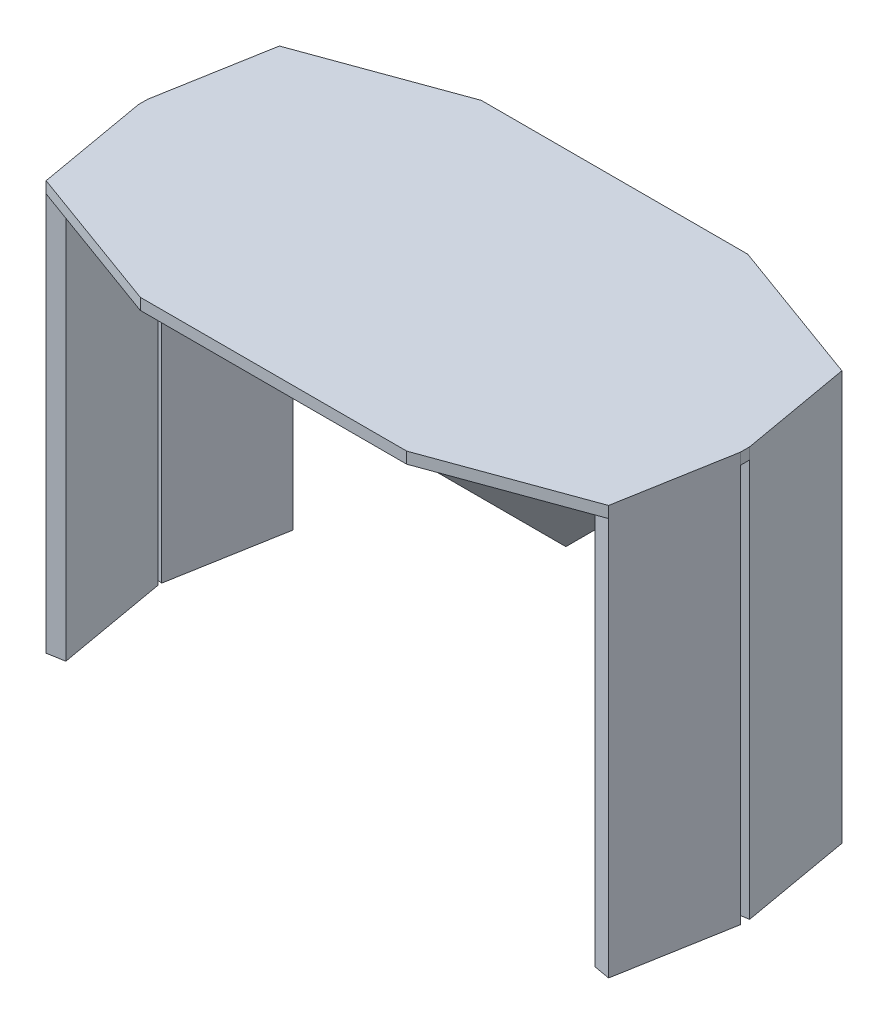
SolidWorks part; units mm, degrees
ref_plane "Front Plane" through (0, 0, 0) normal (0, 0, 1) x (1, 0, 0)
ref_plane "Top Plane" through (0, 0, 0) normal (0, 1, 0) x (1, 0, 0)
ref_plane "Right Plane" through (0, 0, 0) normal (1, 0, 0) x (0, 0, -1)
sketch "Sketch2" plane through (0, 0, 0) normal (1, 0, 0) x (0, 0, -1)
  line L0 (0, 0) -> (20, 28.563)
  line L1 (20, 28.563) -> (-20, 28.563)
  line L2 (-20, 28.563) -> (0, 0)
  dimension "D1" = 55
  dimension "D2" = 55
  dimension "D3" = 40
extrude "Boss-Extrude1" add sketch "Sketch2" along normal blind 100
sketch "Sketch3" plane through (0, 28.563, 0) normal (0, 1, 0) x (1, 0, 0)
  line L0 (96.527, 20) -> (100, 0.3038)
  line L1 (100, 20) -> (0, 20) construction
  line L2 (100, 20) -> (100, -20) construction
  line L3 (0, 0.3038) -> (3.473, 20)
  line L4 (0, 20) -> (0, -20) construction
  line L5 (0, 0) -> (100, 0) construction
  line L6 (96.527, -20) -> (100, -0.3038)
  line L7 (0, -0.3038) -> (3.473, -20)
  line L8 (0, 0.3038) -> (0, 20)
  line L9 (0, 20) -> (3.473, 20)
  line L10 (96.527, 20) -> (100, 20)
  line L11 (100, 20) -> (100, 0.3038)
  line L12 (100, -0.3038) -> (100, -20)
  line L13 (100, -20) -> (96.527, -20)
  line L14 (3.473, -20) -> (0, -20)
  line L15 (0, -20) -> (0, -0.3038)
  dimension "D1" = 20
  dimension "D2" = 20
  dimension "D3" = 10
  dimension "D4" = 10
extrude "Cut-Extrude1" cut sketch "Sketch3" against normal up to vertex
sketch "Sketch4" plane through (0, 28.563, 0) normal (0, 1, 0) x (1, 0, 0)
  line L0 (3.473, 20) -> (0.5185, 20.5209)
  line L1 (0.5185, 20.5209) -> (-2.9544, 0.8248)
  line L2 (-2.9544, 0.8248) -> (0, 0.3038)
  line L3 (0, 0.3038) -> (3.473, 20) construction
  line L8 (3.473, 20) -> (0, 0.3038)
  line L10 (50, 20) -> (50, -20) construction
  line L11 (96.527, 20) -> (3.473, 20) construction
  line L12 (96.527, -20) -> (3.473, -20) construction
  line L13 (0, 0) -> (100, 0) construction
  line L14 (0, 0.3038) -> (0, -0.3038) construction
  line L15 (100, 0.3038) -> (100, -0.3038) construction
  line L16 (96.527, 20) -> (100, 0.3038)
  line L17 (102.9544, 0.8248) -> (100, 0.3038)
  line L18 (99.4815, 20.5209) -> (102.9544, 0.8248)
  line L19 (96.527, 20) -> (99.4815, 20.5209)
  line L20 (96.527, -20) -> (99.4815, -20.5209)
  line L21 (99.4815, -20.5209) -> (102.9544, -0.8248)
  line L22 (102.9544, -0.8248) -> (100, -0.3038)
  line L23 (96.527, -20) -> (100, -0.3038)
  line L24 (3.473, -20) -> (0, -0.3038)
  line L25 (-2.9544, -0.8248) -> (0, -0.3038)
  line L26 (0.5185, -20.5209) -> (-2.9544, -0.8248)
  line L27 (3.473, -20) -> (0.5185, -20.5209)
  dimension "D1" = 3
  dimension "D4" = 3
extrude "Boss-Extrude2" add sketch "Sketch4" against normal blind 70 separate body
sketch "Sketch7" plane through (0, 0, 0) normal (0, 0, 1) x (1, 0, 0)
  line L0 (0, 28.563) -> (28.563, 0)
  line L1 (100, 0) -> (0, 0) construction
  line L2 (28.563, 0) -> (0, 0)
  line L3 (0, 0) -> (0, 28.563)
  line L5 (100, 28.563) -> (100, 0)
  line L6 (100, 0) -> (71.437, 0)
  line L7 (71.437, 0) -> (100, 28.563)
  dimension "D1" = 45
  dimension "D2" = 45
extrude "Cut-Extrude2" cut sketch "Sketch7" against normal up to vertex and the other way up to vertex
sketch "Sketch8" plane through (0, 28.563, 0) normal (0, 1, 0) x (1, 0, 0)
  line L0 (0.5185, 20.5209) -> (26.562, 30)
  line L1 (26.562, 30) -> (73.438, 30)
  line L2 (73.438, 30) -> (99.4815, 20.5209)
  line L3 (0.5185, 20.5209) -> (-2.9544, 0.8248)
  line L4 (-2.9544, 0.8248) -> (-2.9544, -0.8248)
  line L5 (-2.9544, -0.8248) -> (0.5185, -20.5209)
  line L6 (99.4815, 20.5209) -> (102.9544, 0.8248)
  line L7 (96.527, 20) -> (3.473, 20) construction
  line L8 (102.9544, 0.8248) -> (102.9544, -0.8248)
  line L12 (99.4815, -20.5209) -> (73.438, -30)
  line L13 (73.438, -30) -> (26.562, -30)
  line L14 (26.562, -30) -> (0.5185, -20.5209)
  line L15 (96.527, -20) -> (3.473, -20) construction
  line L16 (102.9544, -0.8248) -> (99.4815, -20.5209)
  dimension "D1" = 20
  dimension "D2" = 20
  dimension "D3" = 10
  dimension "D4" = 10
  dimension "D5" = 20
  dimension "D6" = 20
extrude "Boss-Extrude4" add sketch "Sketch8" along normal blind 2
